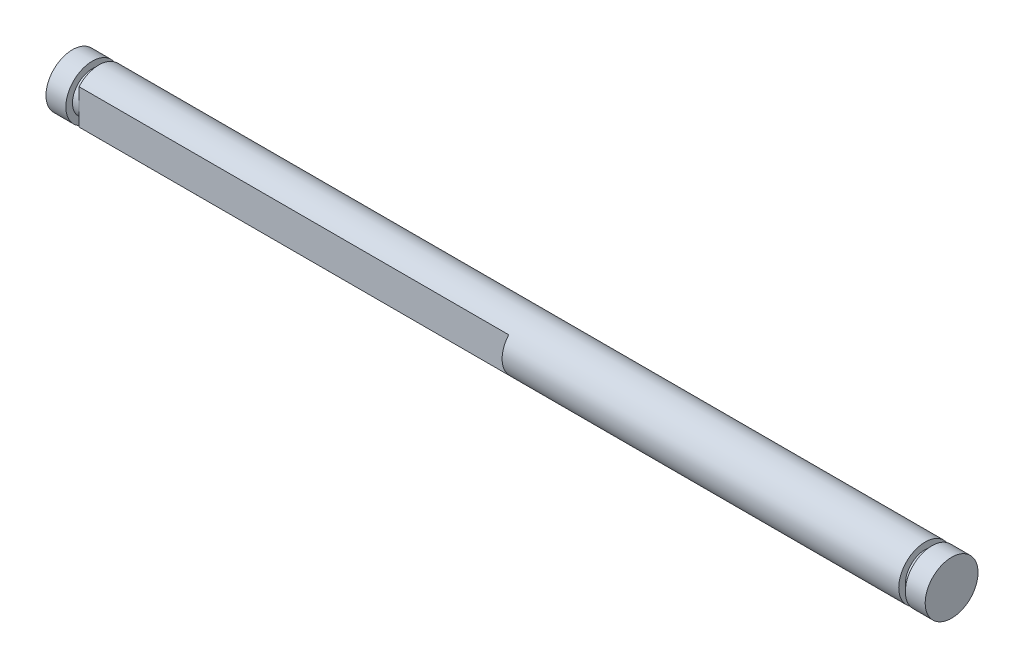
SolidWorks part; units mm, degrees
material "6061-T6 (SS)"
ref_plane "Alzado" through (0, 0, 0) normal (0, 0, 1) x (1, 0, 0)
ref_plane "Planta" through (0, 0, 0) normal (0, 1, 0) x (1, 0, 0)
ref_plane "Vista lateral" through (0, 0, 0) normal (1, 0, 0) x (0, 0, -1)
sketch "Croquis1" plane through (0, 0, 0) normal (0, 1, 0) x (1, 0, 0)
  line L0 (-66.5, 0) -> (66.5, 0) construction
  line L1 (-66.5, 0) -> (-66.5, 4)
  line L2 (-66.5, 4) -> (-63.5, 4)
  line L3 (-63.5, 4) -> (-63.5, 3)
  line L4 (-63.5, 3) -> (-62.5, 3)
  line L5 (-62.5, 3) -> (-62.5, 4)
  line L6 (-62.5, 4) -> (62.5, 4)
  line L7 (62.5, 4) -> (62.5, 3)
  line L8 (62.5, 3) -> (63.5, 3)
  line L9 (63.5, 3) -> (63.5, 4)
  line L10 (63.5, 4) -> (66.5, 4)
  line L11 (66.5, 4) -> (66.5, 0)
  line L12 (-66.5, 0) -> (66.5, 0)
  point P3 (0, 0)
  point P14 (-63.5, 3.5)
  point P20 (0, 4)
  dimension "D1" = 125
  dimension "D2" = 1
  dimension "D3" = 8
  dimension "D4" = 6
  dimension "D5" = 3
revolve "Revolución1" add sketch "Croquis1" angle 360 about L0
sketch "Croquis2" plane through (0, 0, 0) normal (0, 1, 0) x (1, 0, 0)
  line L0 (-62.5, 3) -> (-62.5, -3) construction
  line L1 (-62.5, -4) -> (2.5, -4)
  line L2 (-62.5, -4) -> (-62.5, -3)
  line L3 (-62.5, -3) -> (2.5, -3)
  line L4 (2.5, -4) -> (2.5, -3)
  dimension "D1" = 1
  dimension "D2" = 65
extrude "Cortar-Extruir1" cut sketch "Croquis2" against normal through all both and the other way through all
